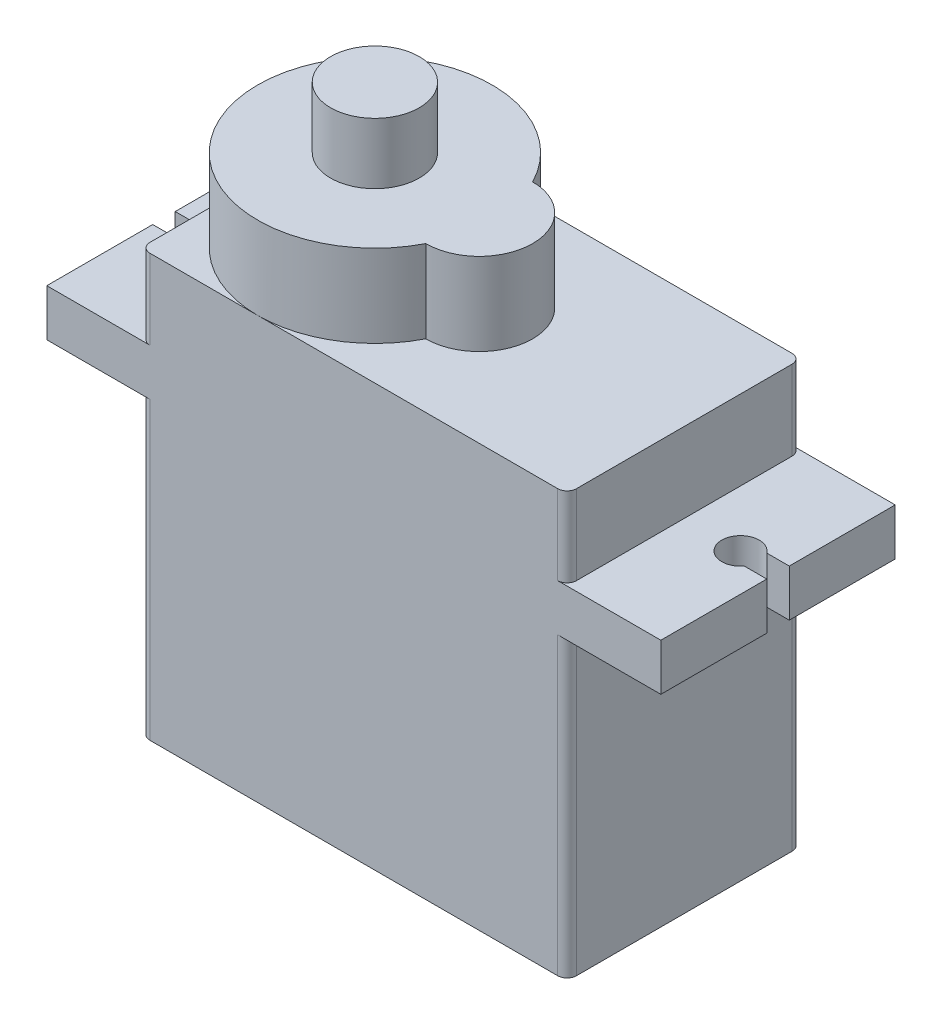
SolidWorks part; units mm, degrees
ref_plane "Front Plane" through (0, 0, 0) normal (0, 0, 1) x (1, 0, 0)
ref_plane "Top Plane" through (0, 0, 0) normal (0, 1, 0) x (1, 0, 0)
ref_plane "Right Plane" through (0, 0, 0) normal (1, 0, 0) x (0, 0, -1)
sketch "Sketch1" plane through (0, 0, 0) normal (0, 1, 0) x (1, 0, 0)
  line L1 (0, 0) -> (22.75, 0)
  line L2 (0, 0) -> (0, -12.5)
  line L3 (0, -12.5) -> (22.75, -12.5)
  line L4 (22.75, 0) -> (22.75, -12.5)
  dimension "D1" = 22.75
  dimension "D2" = 12.5
extrude "Boss-Extrude1" add sketch "Sketch1" along normal blind 22.5
sketch "Sketch2" plane through (0, 22.5, 0) normal (0, 1, 0) x (1, 0, 0)
  line L0 (11.8124, -9.1) -> (11.8124, -3.4) construction
  line L1 (0, 0) -> (0, -12.5) construction
  line L2 (0, -12.5) -> (22.75, -12.5) construction
  line L3 (22.75, 0) -> (0, 0) construction
  line L4 (11.8124, -9.1) -> (0, -9.1) construction
  line L5 (11.8124, -3.4) -> (0, -3.4) construction
  arc A0 (11.8124, -3.4) -> (11.8124, -9.1) centre (6.25, -6.25) ccw
  arc A1 (11.8124, -3.4) -> (11.8124, -9.1) centre (11.8124, -6.25) cw
  dimension "D1" = 5.7
extrude "Boss-Extrude2" add sketch "Sketch2" along normal blind 4.4
sketch "Sketch3" plane through (0, 26.9, 0) normal (0, 1, 0) x (1, 0, 0)
  circle A0 centre (6.25, -6.25) radius 2.365
  arc A1 (11.8124, -3.4) -> (11.8124, -9.1) centre (6.25, -6.25) ccw construction
  dimension "D1" = 4.73
extrude "Boss-Extrude3" add sketch "Sketch3" along normal blind 3.25
sketch "Sketch4" plane through (22.75, 0, 0) normal (1, 0, 0) x (0, 0, -1)
  line L0 (-12.5, 22.5) -> (-12.5, 0) construction
  line L1 (-12.5, 18.25) -> (0, 18.25)
  line L2 (-12.5, 18.25) -> (-12.5, 15.75)
  line L3 (-12.5, 15.75) -> (0, 15.75)
  line L4 (0, 18.25) -> (0, 15.75)
  line L5 (0, 22.5) -> (0, 0) construction
  line L6 (-12.5, 22.5) -> (0, 22.5) construction
  dimension "D1" = 2.5
  dimension "D2" = 6.75
extrude "Boss-Extrude4" add sketch "Sketch4" along normal blind 5
sketch "Sketch5" plane through (0, 0, 0) normal (-1, 0, 0) x (0, 0, 1)
  line L0 (0, 22.5) -> (0, 0) construction
  line L1 (0, 18.25) -> (12.5, 18.25)
  line L2 (0, 18.25) -> (0, 15.75)
  line L3 (0, 15.75) -> (12.5, 15.75)
  line L4 (12.5, 18.25) -> (12.5, 15.75)
  line L5 (12.5, 22.5) -> (12.5, 0) construction
  line L6 (0, 22.5) -> (6.25, 22.5) construction
  dimension "D1" = 2.5
  dimension "D2" = 6.75
extrude "Boss-Extrude5" add sketch "Sketch5" along normal blind 5
sketch "Sketch6" plane through (0, 18.25, 0) normal (0, 1, 0) x (1, 0, 0)
  line L0 (-3, -6.25) -> (-5, -6.25) construction
  line L1 (-5, -12.5) -> (-5, 0) construction
  line L2 (25.75, -6.25) -> (27.75, -6.25) construction
  line L3 (27.75, 0) -> (27.75, -12.5) construction
  line L4 (27.75, -5.65) -> (27.75, -6.85)
  line L5 (27.75, -6.85) -> (26.55, -6.85)
  line L6 (26.55, -5.65) -> (27.75, -5.65)
  line L7 (26.55, -6.85) -> (26.55, -5.65) construction
  line L8 (-3.8, -5.65) -> (-3.8, -6.85) construction
  line L9 (-5, -6.85) -> (-5, -5.65)
  line L10 (-5, -5.65) -> (-3.8, -5.65)
  line L11 (-5, -6.85) -> (-3.8, -6.85)
  arc A0 (-3.8, -5.65) -> (-3.8, -6.85) centre (-3, -6.25) cw
  arc A2 (26.55, -6.85) -> (26.55, -5.65) centre (25.75, -6.25) cw
  point P10 (27.75, -6.25)
  dimension "D1" = 1
  dimension "D3" = 1.2
  dimension "D2" = 2
extrude "Cut-Extrude1" cut sketch "Sketch6" against normal through all
fillet "Fillet1" radius 0.5 8 edges at (0, 7.875, 0) (22.75, 7.875, 0) (22.75, 20.375, 0) (0, 20.375, 0) (22.75, 20.375, 12.5) (22.75, 7.875, 12.5) (0, 7.875, 12.5) (0, 20.375, 12.5)
ref_plane "Plane1" through (0, 0, 6.25) normal (0, 0, -1) x (-1, 0, 0)
ref_plane "Plane2" through (11.375, 0, 0) normal (1, 0, 0) x (0, 0, -1)
